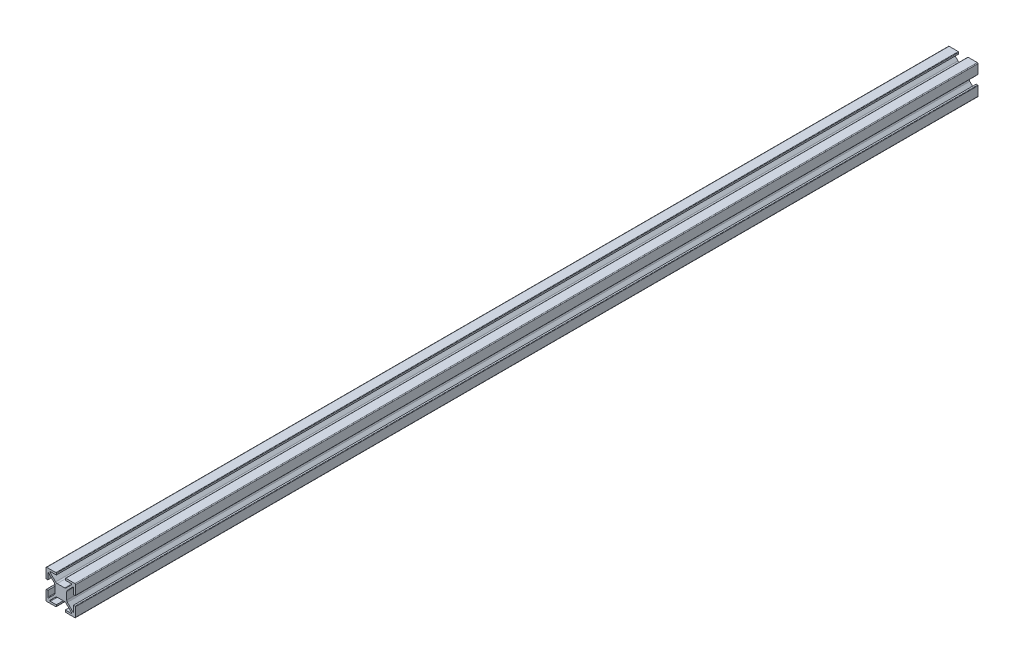
SolidWorks part; units mm, degrees
ref_plane "Front Plane" through (0, 0, 0) normal (0, 0, 1) x (1, 0, 0)
ref_plane "Top Plane" through (0, 0, 0) normal (0, 1, 0) x (1, 0, 0)
ref_plane "Right Plane" through (0, 0, 0) normal (1, 0, 0) x (0, 0, -1)
sketch "Sketch1" plane through (0, 0, 0) normal (0, 0, 1) x (1, 0, 0)
  line L0 (-9.6769, -5.8863) -> (-13.4255, -2.1377)
  line L1 (-13.8648, -1.0771) -> (-13.8648, 3.8418)
  line L2 (-13.4255, 4.9025) -> (-9.6769, 8.651)
  line L3 (-9.1648, 8.4389) -> (-9.1648, 4.4324)
  line L4 (-7.8648, 4.7324) -> (-7.8648, 10.8824)
  line L5 (-8.3648, 11.3824) -> (-14.5148, 11.3824)
  line L6 (-14.8148, 10.0824) -> (-10.8083, 10.0824)
  line L7 (-10.5962, 9.5702) -> (-14.3447, 5.8217)
  line L8 (-15.4054, 5.3824) -> (-20.3242, 5.3824)
  line L9 (-21.3849, 5.8217) -> (-25.1334, 9.5702)
  line L10 (-24.9213, 10.0824) -> (-20.9148, 10.0824)
  line L11 (-21.2148, 11.3824) -> (-27.3648, 11.3824)
  line L12 (-27.8648, 10.8824) -> (-27.8648, 4.7324)
  line L13 (-26.5648, 4.4324) -> (-26.5648, 8.4389)
  line L14 (-26.0527, 8.651) -> (-22.3041, 4.9025)
  line L15 (-21.8648, 3.8418) -> (-21.8648, -1.0771)
  line L16 (-22.3041, -2.1377) -> (-26.0527, -5.8863)
  line L17 (-26.5648, -5.6741) -> (-26.5648, -1.6676)
  line L18 (-27.8648, -1.9676) -> (-27.8648, -8.1176)
  line L19 (-27.3648, -8.6176) -> (-21.2148, -8.6176)
  line L20 (-20.9148, -7.3176) -> (-24.9213, -7.3176)
  line L21 (-25.1334, -6.8055) -> (-21.3849, -3.057)
  line L22 (-20.3242, -2.6176) -> (-15.4054, -2.6176)
  line L23 (-14.3447, -3.057) -> (-10.5962, -6.8055)
  line L24 (-10.8083, -7.3176) -> (-14.8148, -7.3176)
  line L25 (-14.8148, -7.3176) -> (-14.8148, -8.3176)
  line L26 (-14.5148, -8.6176) -> (-8.3648, -8.6176)
  line L27 (-7.8648, -8.1176) -> (-7.8648, -1.9676)
  line L28 (-9.1648, -1.6676) -> (-8.1648, -1.6676)
  line L29 (-9.1648, -1.6676) -> (-9.1648, -5.6741)
  line L30 (-20.9148, 11.0824) -> (-20.9148, 10.0824)
  line L31 (-27.5648, -1.6676) -> (-26.5648, -1.6676)
  line L32 (-14.8148, 11.0824) -> (-14.8148, 10.0824)
  line L33 (-27.5648, 4.4324) -> (-26.5648, 4.4324)
  line L34 (-20.9148, -7.3176) -> (-20.9148, -8.3176)
  line L35 (-9.1648, 4.4324) -> (-8.1648, 4.4324)
  arc A0 (-9.6769, -5.8863) -> (-9.1648, -5.6741) centre (-9.4648, -5.6741) ccw
  arc A1 (-13.8648, -1.0771) -> (-13.4255, -2.1377) centre (-12.3648, -1.0771) ccw
  arc A2 (-13.4255, 4.9025) -> (-13.8648, 3.8418) centre (-12.3648, 3.8418) ccw
  arc A3 (-9.1648, 8.4389) -> (-9.6769, 8.651) centre (-9.4648, 8.4389) ccw
  arc A4 (-7.8648, 10.8824) -> (-8.3648, 11.3824) centre (-8.3648, 10.8824) ccw
  arc A5 (-10.5962, 9.5702) -> (-10.8083, 10.0824) centre (-10.8083, 9.7824) ccw
  arc A6 (-15.4054, 5.3824) -> (-14.3447, 5.8217) centre (-15.4054, 6.8824) ccw
  arc A7 (-21.3849, 5.8217) -> (-20.3242, 5.3824) centre (-20.3242, 6.8824) ccw
  arc A8 (-24.9213, 10.0824) -> (-25.1334, 9.5702) centre (-24.9213, 9.7824) ccw
  arc A9 (-27.3648, 11.3824) -> (-27.8648, 10.8824) centre (-27.3648, 10.8824) ccw
  arc A10 (-26.0527, 8.651) -> (-26.5648, 8.4389) centre (-26.2648, 8.4389) ccw
  arc A11 (-21.8648, 3.8418) -> (-22.3041, 4.9025) centre (-23.3648, 3.8418) ccw
  arc A12 (-22.3041, -2.1377) -> (-21.8648, -1.0771) centre (-23.3648, -1.0771) ccw
  arc A13 (-26.5648, -5.6741) -> (-26.0527, -5.8863) centre (-26.2648, -5.6741) ccw
  arc A14 (-27.8648, -8.1176) -> (-27.3648, -8.6176) centre (-27.3648, -8.1176) ccw
  arc A15 (-25.1334, -6.8055) -> (-24.9213, -7.3176) centre (-24.9213, -7.0176) ccw
  arc A16 (-20.3242, -2.6176) -> (-21.3849, -3.057) centre (-20.3242, -4.1176) ccw
  arc A17 (-14.3447, -3.057) -> (-15.4054, -2.6176) centre (-15.4054, -4.1176) ccw
  arc A18 (-10.8083, -7.3176) -> (-10.5962, -6.8055) centre (-10.8083, -7.0176) ccw
  arc A19 (-8.3648, -8.6176) -> (-7.8648, -8.1176) centre (-8.3648, -8.1176) ccw
  arc A20 (-27.5648, 4.4324) -> (-27.8648, 4.7324) centre (-27.5648, 4.7324) cw
  arc A21 (-27.5648, -1.6676) -> (-27.8648, -1.9676) centre (-27.5648, -1.9676) ccw
  arc A22 (-20.9148, -8.3176) -> (-21.2148, -8.6176) centre (-21.2148, -8.3176) cw
  arc A23 (-14.8148, -8.3176) -> (-14.5148, -8.6176) centre (-14.5148, -8.3176) ccw
  arc A24 (-8.1648, -1.6676) -> (-7.8648, -1.9676) centre (-8.1648, -1.9676) cw
  arc A25 (-8.1648, 4.4324) -> (-7.8648, 4.7324) centre (-8.1648, 4.7324) ccw
  arc A26 (-14.8148, 11.0824) -> (-14.5148, 11.3824) centre (-14.5148, 11.0824) cw
  arc A27 (-20.9148, 11.0824) -> (-21.2148, 11.3824) centre (-21.2148, 11.0824) ccw
  point P96 (-17.8648, 1.3824)
  dimension "D1" = 4.9189
  dimension "D2" = 4.9189
extrude "Boss-Extrude1" add sketch "Sketch1" along normal blind 610
